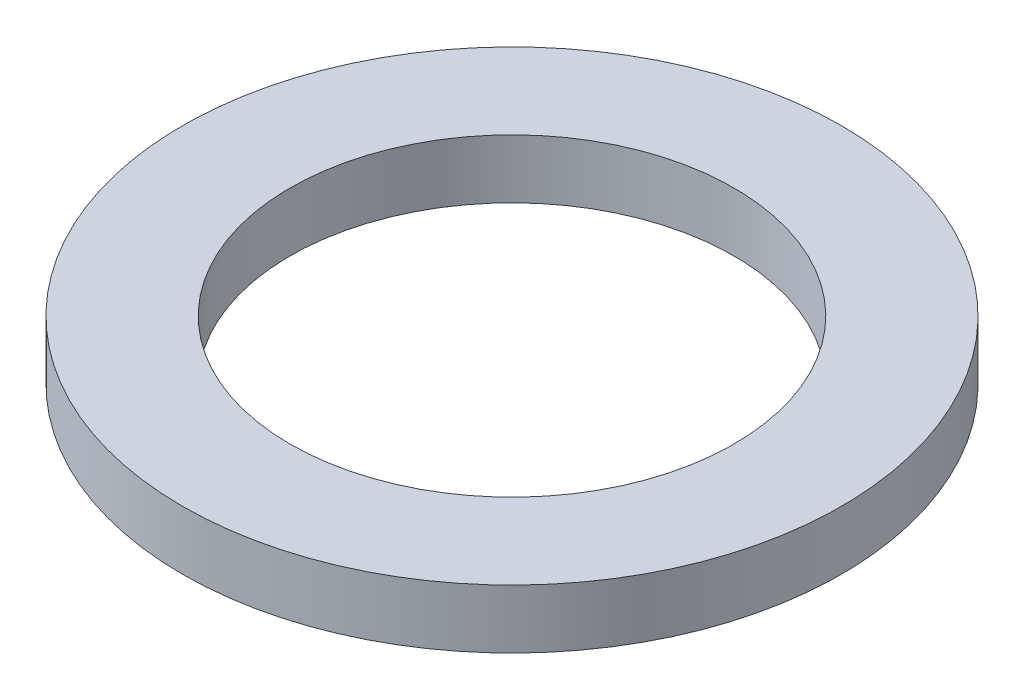
SolidWorks part; units mm, degrees
material "Nylon 101"
ref_plane "Front Plane" through (0, 0, 0) normal (0, 0, 1) x (1, 0, 0)
ref_plane "Top Plane" through (0, 0, 0) normal (0, 1, 0) x (1, 0, 0)
ref_plane "Right Plane" through (0, 0, 0) normal (1, 0, 0) x (0, 0, -1)
sketch "Sketch1" plane through (0, 0, 0) normal (0, 1, 0) x (1, 0, 0)
  circle A0 centre (0, 0) radius 6.4135
  circle A1 centre (0, 0) radius 9.525
  dimension "D1" = 12.827
  dimension "D2" = 19.05
extrude "Boss-Extrude1" add sketch "Sketch1" along normal blind 1.7018
